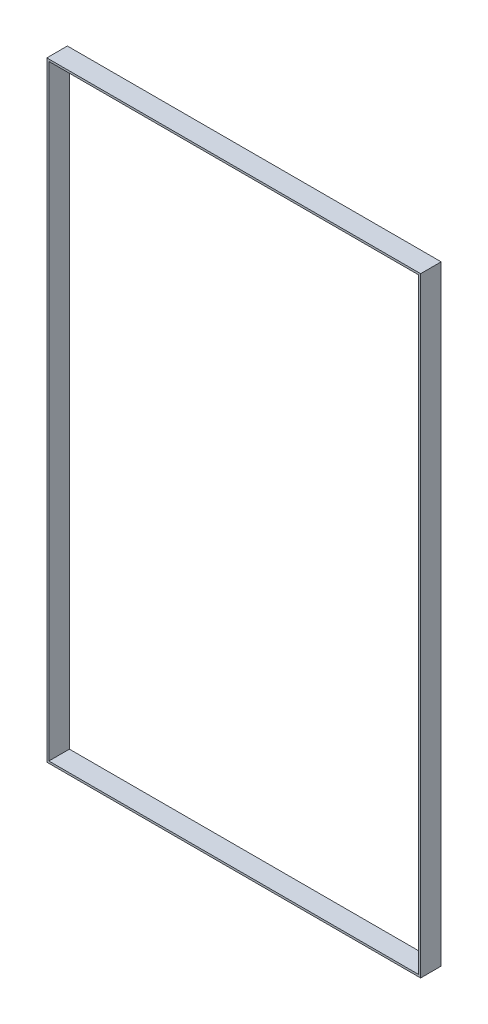
SolidWorks part; units mm, degrees
ref_plane "Plano frontal" through (0, 0, 0) normal (0, 0, 1) x (1, 0, 0)
ref_plane "Plano superior" through (0, 0, 0) normal (0, 1, 0) x (1, 0, 0)
ref_plane "Plano direito" through (0, 0, 0) normal (1, 0, 0) x (0, 0, -1)
sketch "Esboço1" plane through (0, 0, 0) normal (0, 0, 1) x (1, 0, 0)
  line L1 (-90, -147.5) -> (90, -147.5)
  line L2 (-90, -147.5) -> (-90, 147.5)
  line L3 (-90, 147.5) -> (90, 147.5)
  line L4 (90, -147.5) -> (90, 147.5)
  line L5 (-90, -147.5) -> (90, 147.5) construction
  line L6 (-90, 147.5) -> (90, -147.5) construction
  line L7 (-91, -148.5) -> (91, -148.5)
  line L8 (-91, -148.5) -> (-91, 148.5)
  line L9 (-91, 148.5) -> (91, 148.5)
  line L10 (91, -148.5) -> (91, 148.5)
  line L11 (-91, -148.5) -> (91, 148.5) construction
  line L12 (-91, 148.5) -> (91, -148.5) construction
  point P0 (0, 0)
  point P6 (0, 0)
  dimension "D1" = 180
  dimension "D2" = 295
  dimension "D3" = 182
  dimension "D4" = 297
extrude "Ressalto-extrusão1" add sketch "Esboço1" along normal blind 10
